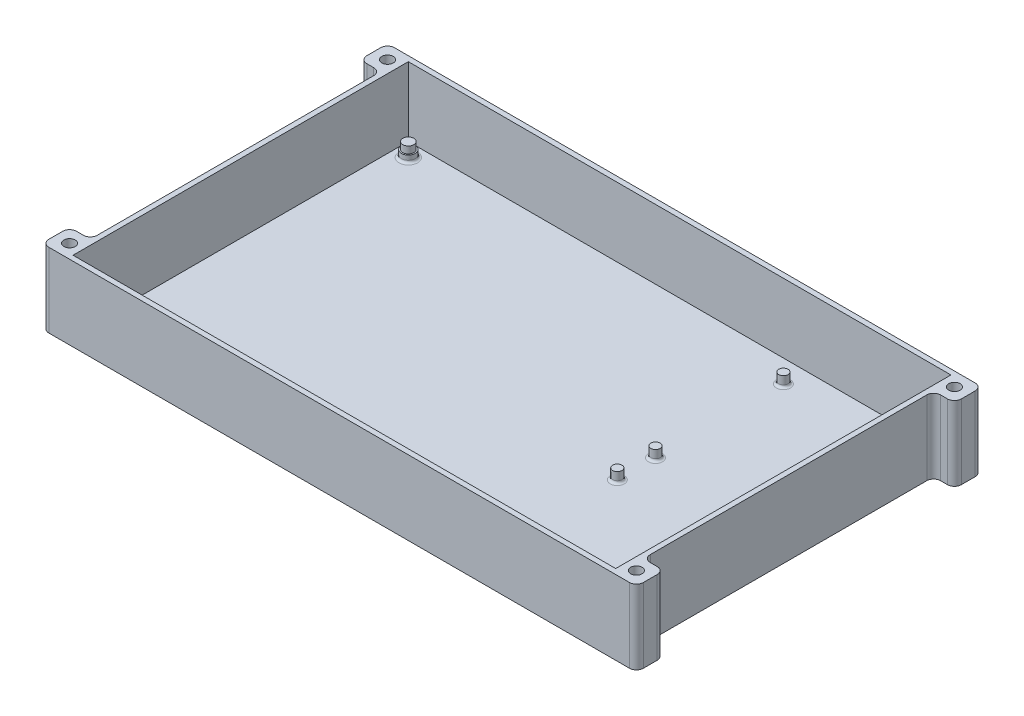
SolidWorks part; units mm, degrees
ref_plane "Front Plane" through (0, 0, 0) normal (0, 0, 1) x (1, 0, 0)
ref_plane "Top Plane" through (0, 0, 0) normal (0, 1, 0) x (1, 0, 0)
ref_plane "Right Plane" through (0, 0, 0) normal (1, 0, 0) x (0, 0, -1)
sketch "Sketch1" plane through (0, 0, 0) normal (0, 1, 0) x (1, 0, 0)
  line L0 (80, 0) -> (80, 1.5) construction
  line L1 (0, 0) -> (160, 0)
  line L2 (0, 0) -> (0, 100)
  line L3 (0, 100) -> (160, 100)
  line L4 (160, 0) -> (160, 100)
  line L5 (80, 1.5) -> (0, 1.5) construction
  line L6 (0, 50) -> (1.5, 50) construction
  line L7 (1.5, 50) -> (1.5, 0) construction
  line L9 (1.5, 1.5) -> (158.5, 1.5)
  line L10 (1.5, 1.5) -> (1.5, 98.5)
  line L11 (1.5, 98.5) -> (158.5, 98.5)
  line L12 (158.5, 1.5) -> (158.5, 98.5)
  dimension "D1" = 100
  dimension "D2" = 160
  dimension "D3" = 157
  dimension "D4" = 97
extrude "Boss-Extrude1" add sketch "Sketch1" along normal blind 20 contours L10 L9 L12 L11 | L2 L1 L4 L3
sketch "Sketch2" plane through (0, 0, 0) normal (0, -1, 0) x (1, 0, 0)
  line L1 (0, 0) -> (160, 0)
  line L2 (0, 0) -> (0, -100)
  line L3 (0, -100) -> (160, -100)
  line L4 (160, 0) -> (160, -100)
extrude "Boss-Extrude2" add sketch "Sketch2" along normal blind 1.5
sketch "Sketch3" plane through (0, 0, 0) normal (0, 1, 0) x (1, 0, 0)
  line L0 (1.5, 1.5) -> (5.5, 1.5) construction
  line L1 (1.5, 1.5) -> (158.5, 1.5) construction
  line L2 (5.5, 1.5) -> (5.5, 5.5) construction
  line L3 (0, 50) -> (160, 50) construction
  line L4 (0, 0) -> (0, 100) construction
  line L5 (160, 0) -> (160, 100) construction
  line L8 (5.5, 5.5) -> (94.5, 5.5) construction
  circle A0 centre (5.5, 5.5) radius 2
  circle A3 centre (5.5, 94.5) radius 2
  circle A4 centre (94.5, 5.5) radius 2
  dimension "D1" = 4
  dimension "D3" = 89
extrude "Boss-Extrude3" add sketch "Sketch3" along normal blind 2
sketch "Sketch4" plane through (0, 2, 0) normal (0, 1, 0) x (1, 0, 0)
  line L0 (0, 50) -> (158.5, 50) construction
  line L1 (0, 0) -> (0, 100) construction
  line L2 (158.5, 1.5) -> (158.5, 98.5) construction
  circle A0 centre (5.5, 5.5) radius 1.6
  circle A1 centre (94.5, 5.5) radius 1.6
  circle A2 centre (5.5, 94.5) radius 1.6
  dimension "D1" = 3.2
  dimension "D2" = 3.2
extrude "Boss-Extrude4" add sketch "Sketch4" along normal blind 2
sketch "Sketch5" plane through (0, 0, 0) normal (0, 1, 0) x (1, 0, 0)
  line L0 (1.5, 50) -> (96.5, 50) construction
  line L1 (1.5, 1.5) -> (1.5, 98.5) construction
  line L2 (96.5, 50) -> (96.5, 98.5) construction
  line L3 (1.5, 98.5) -> (158.5, 98.5) construction
  line L4 (96.5, 74.25) -> (116.5, 74.25) construction
  line L5 (96.5, 50) -> (96.5, 1.5) construction
  line L6 (1.5, 1.5) -> (158.5, 1.5) construction
  line L7 (96.5, 25.75) -> (116.5, 25.75) construction
  line L8 (116.5, 74.25) -> (116.5, 92.0274) construction
  line L9 (116.5, 92.0274) -> (116.5, 55.0274) construction
  line L10 (116.5, 92.0274) -> (153.5, 92.0274) construction
  line L11 (116.5, 55.0274) -> (153.5, 55.0274) construction
  line L12 (116.5, 25.75) -> (116.5, 43.9689) construction
  line L13 (116.5, 43.9689) -> (116.5, 6.9689) construction
  line L14 (116.5, 43.9689) -> (153.5, 43.9689) construction
  line L15 (153.5, 43.9689) -> (153.5, 6.9689) construction
  circle A0 centre (116.5, 92.0274) radius 1.35
  circle A1 centre (116.5, 55.0274) radius 1.35
  circle A2 centre (153.5, 55.0274) radius 1.35
  circle A3 centre (153.5, 92.0274) radius 1.35
  circle A4 centre (116.5, 43.9689) radius 1.35
  circle A5 centre (153.5, 43.9689) radius 1.35
  circle A6 centre (116.5, 6.9689) radius 1.35
  circle A7 centre (153.5, 6.9689) radius 1.35
  dimension "D4" = 2.7
  dimension "D1" = 95
  dimension "D2" = 20
  dimension "D3" = 37
  dimension "D5" = 37
  dimension "D6" = 37
extrude "Boss-Extrude5" add sketch "Sketch5" along normal blind 3
fillet "Fillet1" radius 0.7 11 edges at (153.5, 0, -8.3189) (94.5, 0, -7.5) (116.5, 0, -8.3189) (5.5, 0, -7.5) (5.5, 0, -96.5) (153.5, 0, -45.3189) (116.5, 0, -45.3189) (116.5, 0, -56.3774) (153.5, 0, -56.3774) (153.5, 0, -93.3774) (116.5, 0, -93.3774)
sketch "Sketch8" plane through (0, 20, 0) normal (0, 1, 0) x (1, 0, 0)
  line L0 (0, 100) -> (160, 100) construction
  line L5 (1.5, 100) -> (-6.5, 100)
  line L6 (1.5, 100) -> (1.5, 92)
  line L7 (1.5, 92) -> (-6.5, 92)
  line L8 (-6.5, 100) -> (-6.5, 92)
  line L9 (0, 0) -> (0, 100) construction
  line L10 (80, 100) -> (80, 0) construction
  line L12 (0, 0) -> (160, 0) construction
  line L14 (1.5, 8) -> (-6.5, 8)
  line L15 (-6.5, 0) -> (-6.5, 8)
  line L16 (1.5, 0) -> (-6.5, 0)
  line L17 (1.5, 0) -> (1.5, 8)
  line L18 (158.5, 0) -> (158.5, 8)
  line L19 (158.5, 0) -> (166.5, 0)
  line L20 (166.5, 0) -> (166.5, 8)
  line L21 (158.5, 8) -> (166.5, 8)
  line L22 (158.5, 92) -> (166.5, 92)
  line L23 (166.5, 100) -> (166.5, 92)
  line L24 (158.5, 100) -> (166.5, 100)
  line L25 (158.5, 100) -> (158.5, 92)
  circle A0 centre (-2, 96) radius 1.65
  circle A1 centre (-2, 4) radius 1.65
  circle A2 centre (162, 4) radius 1.65
  circle A3 centre (162, 96) radius 1.65
  dimension "D3" = 3.3
  dimension "D1" = 8
  dimension "D2" = 8
  dimension "D4" = 2
extrude "Boss-Extrude7" add sketch "Sketch8" against normal up to surface (21.5 mm away) up to face at (80, -1.5, -50)
fillet "Fillet2" radius 2 4 edges at (160, 9.25, -92) (160, 9.25, -8) (0, 9.25, -8) (0, 9.25, -92)
sketch "Sketch9" plane through (0, 20, 0) normal (0, 1, 0) x (1, 0, 0)
  line L0 (-6.5, 92) -> (-2, 92) construction
  line L1 (-6.5, 100) -> (-6, 100)
  line L2 (-6.5, 100) -> (-6.5, 92)
  line L3 (-6.5, 92) -> (-6, 92)
  line L4 (-6, 100) -> (-6, 92)
  line L5 (-6.5, 0) -> (166.5, 0) construction
  line L6 (-6.5, 8) -> (-6, 8)
  line L7 (-6.5, 8) -> (-6.5, 0)
  line L8 (-6.5, 0) -> (-6, 0)
  line L9 (-6, 8) -> (-6, 0)
  line L10 (162, 92) -> (166.5, 92) construction
  line L11 (166.5, 8) -> (166, 8)
  line L12 (166.5, 8) -> (166.5, 0)
  line L13 (166.5, 0) -> (166, 0)
  line L14 (166, 8) -> (166, 0)
  line L15 (166.5, 100) -> (166, 100)
  line L16 (166.5, 100) -> (166.5, 92)
  line L17 (166.5, 92) -> (166, 92)
  line L18 (166, 100) -> (166, 92)
  dimension "D1" = 0.5
extrude "Cut-Extrude1" cut sketch "Sketch9" against normal blind 22
fillet "Fillet3" radius 2 8 edges at (-6, 9.25, -92) (-6, 9.25, -100) (-6, 9.25, -8) (-6, 9.25, 0) (166, 9.25, 0) (166, 9.25, -8) (166, 9.25, -92) (166, 9.25, -100)
sketch "Sketch10" plane through (0, -1.5, 0) normal (0, -1, 0) x (1, 0, 0)
  line L0 (80, -100) -> (80, 0) construction
  line L1 (-2, -92.7091) -> (-4.85, -94.3546)
  line L2 (-4.85, -94.3546) -> (-4.85, -97.6454)
  line L3 (-4.85, -97.6454) -> (-2, -99.2909)
  line L4 (-2, -99.2909) -> (0.85, -97.6454)
  line L5 (0.85, -97.6454) -> (0.85, -94.3546)
  line L6 (0.85, -94.3546) -> (-2, -92.7091)
  line L7 (-4, -100) -> (164, -100) construction
  line L8 (164, 0) -> (-4, 0) construction
  line L9 (0, -50) -> (160, -50) construction
  line L10 (0, -10) -> (0, -90) construction
  line L11 (160, -90) -> (160, -10) construction
  line L12 (159.15, -94.3546) -> (162, -92.7091)
  line L13 (159.15, -97.6454) -> (159.15, -94.3546)
  line L14 (162, -99.2909) -> (159.15, -97.6454)
  line L15 (164.85, -97.6454) -> (162, -99.2909)
  line L16 (164.85, -94.3546) -> (164.85, -97.6454)
  line L17 (162, -92.7091) -> (164.85, -94.3546)
  line L18 (159.15, -2.3546) -> (159.15, -5.6454)
  line L19 (162, -0.7091) -> (159.15, -2.3546)
  line L20 (164.85, -2.3546) -> (162, -0.7091)
  line L21 (164.85, -5.6454) -> (164.85, -2.3546)
  line L22 (162, -7.2909) -> (164.85, -5.6454)
  line L23 (159.15, -5.6454) -> (162, -7.2909)
  line L24 (0.85, -5.6454) -> (-2, -7.2909)
  line L25 (0.85, -2.3546) -> (0.85, -5.6454)
  line L26 (-2, -0.7091) -> (0.85, -2.3546)
  line L27 (-4.85, -2.3546) -> (-2, -0.7091)
  line L28 (-4.85, -5.6454) -> (-4.85, -2.3546)
  line L29 (-2, -7.2909) -> (-4.85, -5.6454)
  circle A0 centre (-2, -96) radius 2.85 construction
  point P1 (-0.575, -98.4682)
  dimension "D1" = 5.7
extrude "Cut-Extrude2" cut sketch "Sketch10" against normal blind 2.7
